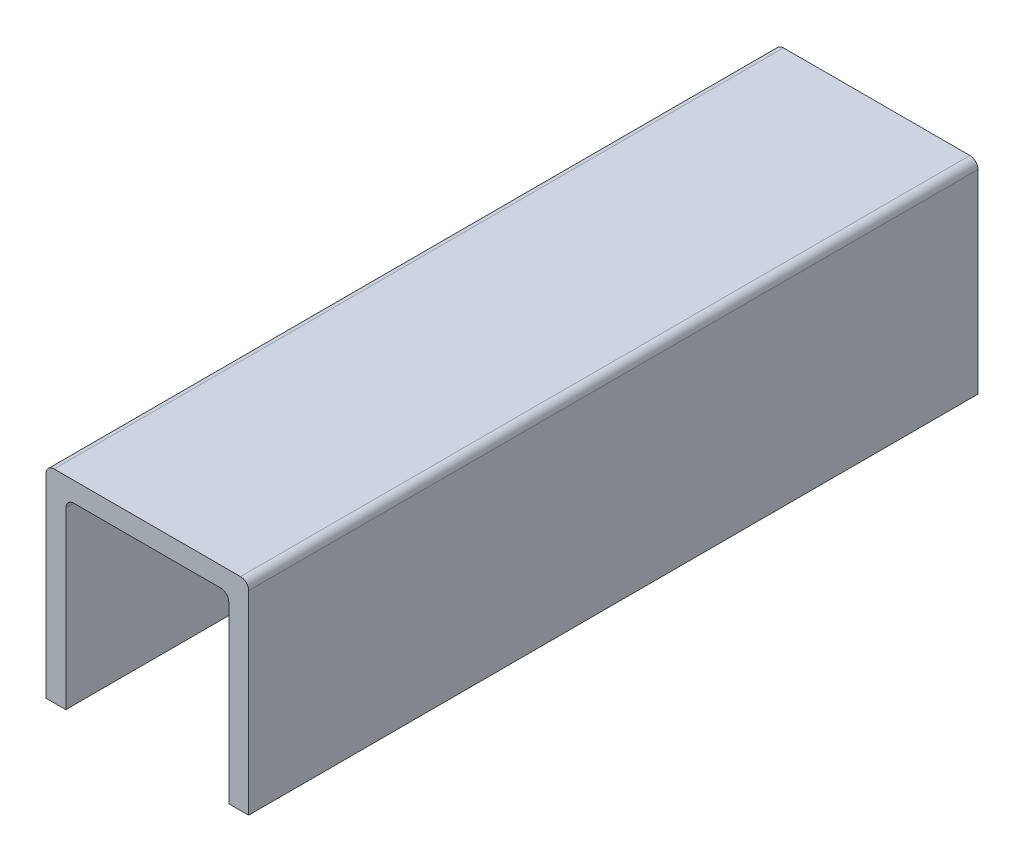
SolidWorks part; units mm, degrees
material "AISI 304"
ref_plane "Front Plane" through (0, 0, 0) normal (0, 0, 1) x (1, 0, 0)
ref_plane "Top Plane" through (0, 0, 0) normal (0, 1, 0) x (1, 0, 0)
ref_plane "Right Plane" through (0, 0, 0) normal (1, 0, 0) x (0, 0, -1)
sketch "Sketch1" plane through (0, 0, 0) normal (0, 0, 1) x (1, 0, 0)
  line L0 (0, 0) -> (0, 50)
  line L1 (0, 50) -> (50, 50)
  line L2 (50, 50) -> (50, 0)
  line L3 (50, 0) -> (45.113, 0)
  line L4 (45.113, 0) -> (45.113, 45.113)
  line L5 (45.113, 45.113) -> (4.887, 45.113)
  line L6 (4.887, 45.113) -> (4.887, 0)
  line L7 (4.887, 0) -> (0, 0)
  line L8 (4.887, 45.113) -> (4.887, 50) construction
  dimension "D1" = 50
  dimension "D2" = 4.887
extrude "Boss-Extrude1" add sketch "Sketch1" along normal blind 180
fillet "Fillet1" radius 2 4 edges at (4.887, 45.113, 90) (45.113, 45.113, 90) (0, 50, 90) (50, 50, 90)
